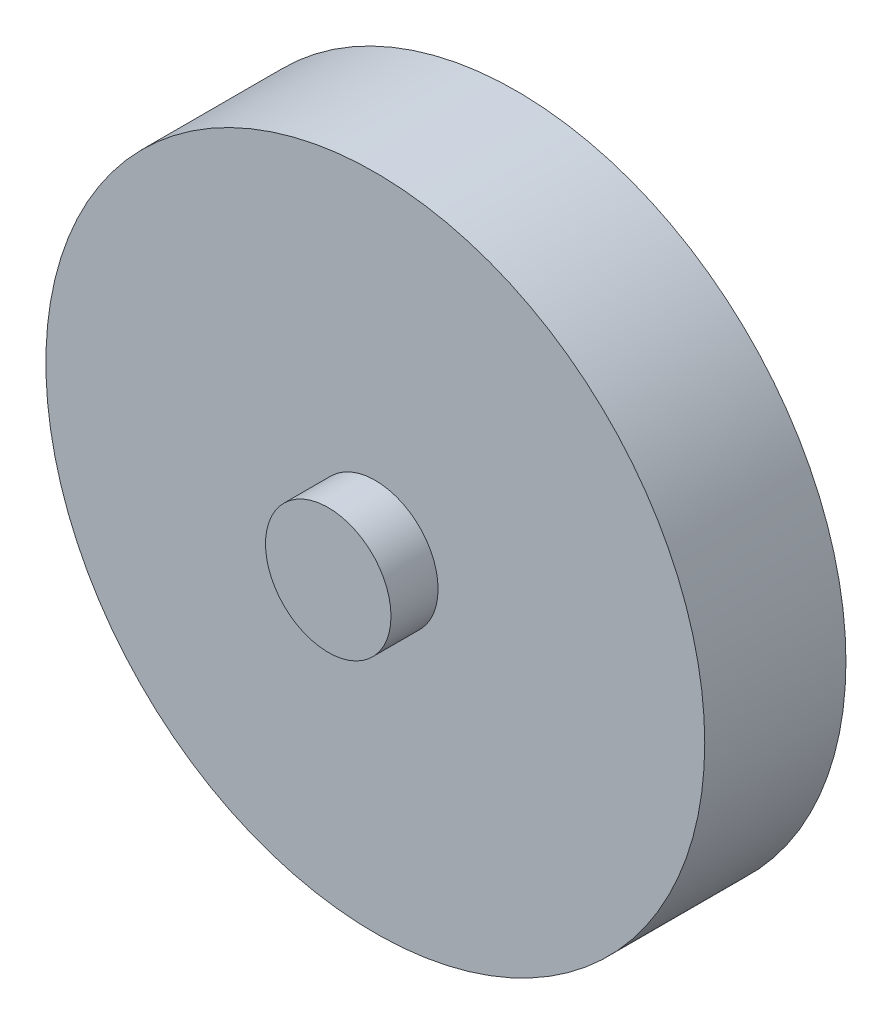
SolidWorks part; units mm, degrees
ref_plane "前视基准面" through (0, 0, 0) normal (0, 0, 1) x (1, 0, 0)
ref_plane "上视基准面" through (0, 0, 0) normal (0, 1, 0) x (1, 0, 0)
ref_plane "右视基准面" through (0, 0, 0) normal (1, 0, 0) x (0, 0, -1)
other "Configuration Table"
sketch "草图1" plane through (0, 0, 0) normal (0, 0, 1) x (1, 0, 0)
  circle A0 centre (0, 0) radius 8
extrude "凸台-拉伸1" add sketch "草图1" along normal blind 24
sketch "草图2" plane through (0, 0, 0) normal (0, 0, 1) x (1, 0, 0)
  circle A0 centre (0, 0) radius 42
extrude "凸台-拉伸2" add sketch "草图2" along normal blind 18
sketch "草图3" plane through (0, 0, 18) normal (0, 0, 1) x (1, 0, 0)
  line L0 (37.3016, 3.8521) -> (37.3889, 3.8612)
  line L1 (37.3016, 2.0353) -> (37.3016, 2.0305)
  arc A0 (41.5984, 5.7942) -> (41.9927, 0.7845) centre (0, 0) cw
  arc A1 (37.3016, 2.0305) -> (37.1592, 3.8374) centre (0, 0) ccw
